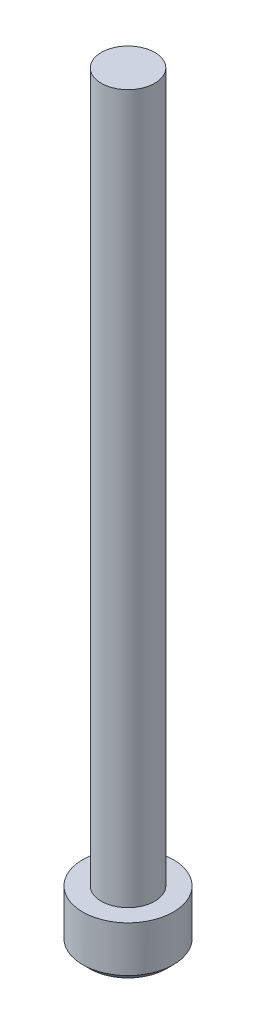
SolidWorks part; units mm, degrees
ref_plane "Front Plane" through (0, 0, 0) normal (0, 0, 1) x (1, 0, 0)
ref_plane "Top Plane" through (0, 0, 0) normal (0, 1, 0) x (1, 0, 0)
ref_plane "Right Plane" through (0, 0, 0) normal (1, 0, 0) x (0, 0, -1)
sketch "Sketch1" plane through (0, 0, 0) normal (0, 1, 0) x (1, 0, 0)
  circle A0 centre (0, 0) radius 6.4
  dimension "D1" = 12.8
extrude "Boss-Extrude1" add sketch "Sketch1" along normal blind 7.45
sketch "Sketch2" plane through (0, 7.45, 0) normal (0, 1, 0) x (1, 0, 0)
  circle A0 centre (0, 0) radius 3.775
  dimension "D1" = 7.55
extrude "Boss-Extrude2" add sketch "Sketch2" along normal blind 100
sketch "Sketch3" plane through (0, 0, 0) normal (0, -1, 0) x (1, 0, 0)
  line L1 (-3.6084, 0) -> (-1.8042, -3.125)
  line L2 (-1.8042, -3.125) -> (1.8042, -3.125)
  line L3 (1.8042, -3.125) -> (3.6084, 0)
  line L4 (3.6084, 0) -> (1.8042, 3.125)
  line L5 (1.8042, 3.125) -> (-1.8042, 3.125)
  line L6 (-1.8042, 3.125) -> (-3.6084, 0)
  circle A0 centre (0, 0) radius 3.125 construction
  dimension "D1" = 6.25
extrude "Cut-Extrude1" cut sketch "Sketch3" against normal blind 5
sketch "Sketch4" plane through (0, 0, 0) normal (1, 0, 0) x (0, 0, -1)
  line L0 (5.4, 0) -> (6.4, 1)
  line L1 (-6.4, 0) -> (6.4, 0) construction
  line L2 (6.4, 0) -> (6.4, 7.45) construction
  line L3 (0, 0) -> (0, 2.4511)
  line L4 (6.4, 1) -> (6.4, 0)
  line L5 (6.4, 0) -> (5.4, 0)
  dimension "D1" = 1
  dimension "D2" = 1
revolve "Cut-Revolve1" cut sketch "Sketch4" angle 360 about L3
